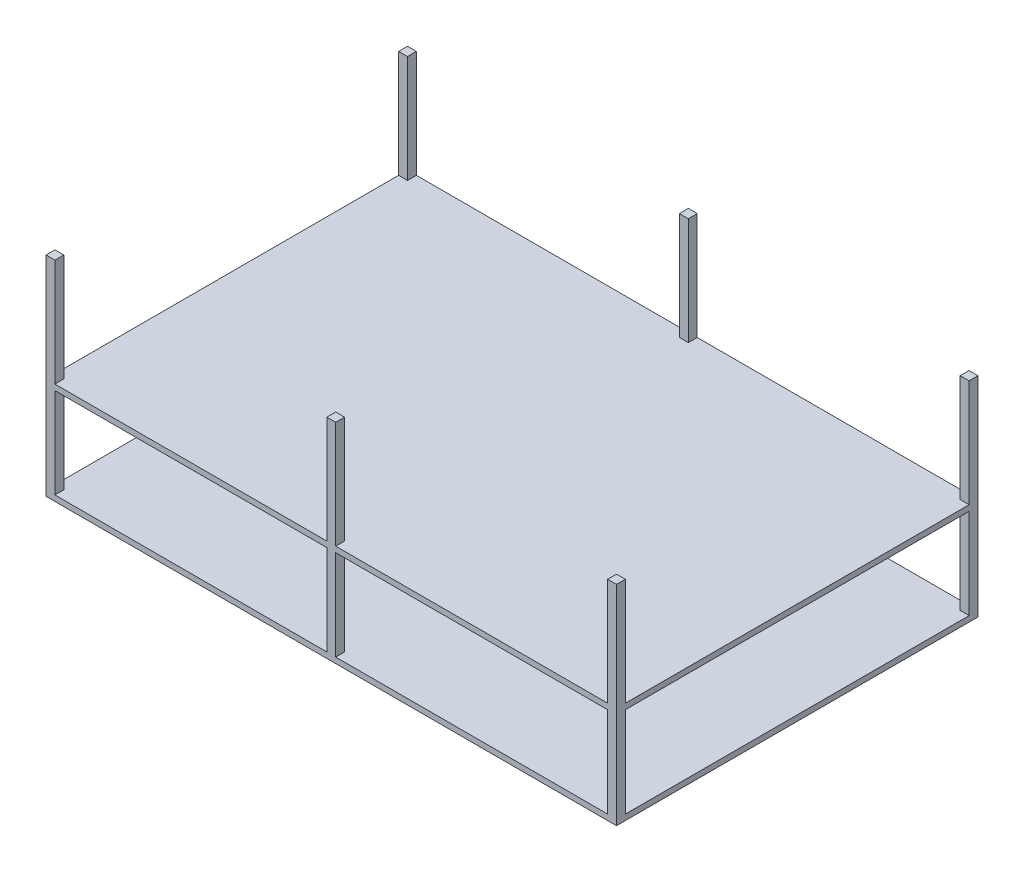
SolidWorks part; units mm, degrees
ref_plane "Front Plane" through (0, 0, 0) normal (0, 0, 1) x (1, 0, 0)
ref_plane "Top Plane" through (0, 0, 0) normal (0, 1, 0) x (1, 0, 0)
ref_plane "Right Plane" through (0, 0, 0) normal (1, 0, 0) x (0, 0, -1)
sketch "Sketch1" plane through (0, 2661.4582, 0) normal (0, -1, 0) x (1, 0, 0)
  line L0 (-9.2336, 757.9374) -> (-9.2336, -1003.3547) construction
  line L1 (-1228.4336, 757.9374) -> (1209.9664, 757.9374) construction
  line L2 (-1228.4336, 8.6374) -> (529.5248, 8.6374) construction
  line L3 (-1228.4336, -740.6626) -> (-1228.4336, 757.9374) construction
  line L4 (1233.4664, 781.4374) -> (1273.4664, 781.4374)
  line L5 (-1251.9336, 781.4374) -> (-1291.9336, 781.4374)
  line L6 (-1251.9336, 781.4374) -> (-1251.9336, 821.4374)
  line L7 (-1251.9336, 821.4374) -> (-1291.9336, 821.4374)
  line L8 (-1291.9336, 781.4374) -> (-1291.9336, 821.4374)
  line L9 (-29.2336, 821.4374) -> (10.7664, 821.4374)
  line L10 (-29.2336, 821.4374) -> (-29.2336, 781.4374)
  line L11 (-29.2336, 781.4374) -> (10.7664, 781.4374)
  line L12 (10.7664, 821.4374) -> (10.7664, 781.4374)
  line L13 (1233.4664, 781.4374) -> (1233.4664, 821.4374)
  line L14 (1233.4664, 821.4374) -> (1273.4664, 821.4374)
  line L15 (1273.4664, 781.4374) -> (1273.4664, 821.4374)
  line L16 (-1251.9336, -764.1626) -> (-1291.9336, -764.1626)
  line L17 (-1251.9336, -764.1626) -> (-1251.9336, -804.1626)
  line L18 (-1251.9336, -804.1626) -> (-1291.9336, -804.1626)
  line L19 (-1291.9336, -764.1626) -> (-1291.9336, -804.1626)
  line L20 (-29.2336, -764.1626) -> (10.7664, -764.1626)
  line L21 (10.7664, -804.1626) -> (10.7664, -764.1626)
  line L22 (-29.2336, -804.1626) -> (10.7664, -804.1626)
  line L23 (-29.2336, -804.1626) -> (-29.2336, -764.1626)
  line L24 (1233.4664, -764.1626) -> (1273.4664, -764.1626)
  line L25 (1273.4664, -764.1626) -> (1273.4664, -804.1626)
  line L26 (1233.4664, -804.1626) -> (1273.4664, -804.1626)
  line L27 (1233.4664, -764.1626) -> (1233.4664, -804.1626)
  point P16 (-9.2336, 781.4374)
  dimension "D1" = 40
  dimension "D2" = 40
  dimension "D3" = 63.5
  dimension "D4" = 63.5
extrude "Boss-Extrude1" add sketch "Sketch1" along normal blind 939.8
sketch "Sketch2" plane through (0, 1721.6582, 0) normal (0, -1, 0) x (1, 0, 0)
  line L1 (-1291.9336, 821.4374) -> (1273.4664, 821.4374)
  line L2 (-1291.9336, 821.4374) -> (-1291.9336, -804.1626)
  line L3 (-1291.9336, -804.1626) -> (1273.4664, -804.1626)
  line L4 (1273.4664, 821.4374) -> (1273.4664, -804.1626)
extrude "Boss-Extrude2" add sketch "Sketch2" against normal blind 25.4
ref_plane "Plane1" through (0, 2153.4582, 0) normal (0, -1, 0) x (1, 0, 0)
sketch "Sketch3" plane through (0, 2153.4582, 0) normal (0, -1, 0) x (1, 0, 0)
  line L1 (-1291.9336, 821.4374) -> (1273.4664, 821.4374)
  line L2 (-1291.9336, 821.4374) -> (-1291.9336, -804.1626)
  line L3 (-1291.9336, -804.1626) -> (1273.4664, -804.1626)
  line L4 (1273.4664, 821.4374) -> (1273.4664, -804.1626)
extrude "Boss-Extrude3" add sketch "Sketch3" against normal blind 25.4
